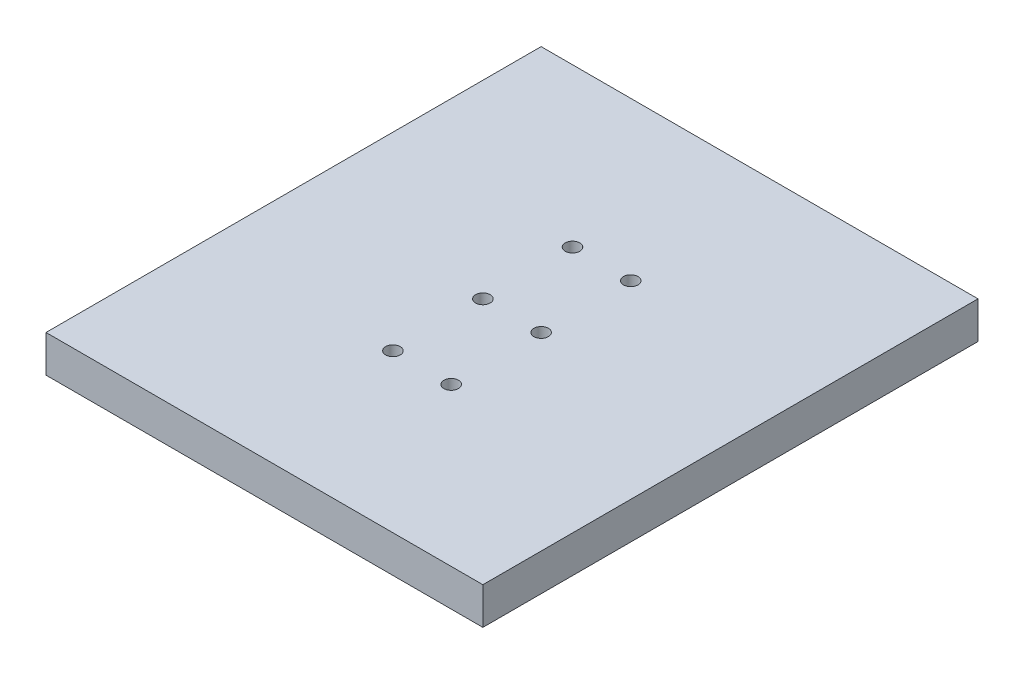
SolidWorks part; units mm, degrees
material "Aleación 1060"
ref_plane "Alzado" through (0, 0, 0) normal (0, 0, 1) x (1, 0, 0)
ref_plane "Planta" through (0, 0, 0) normal (0, 1, 0) x (1, 0, 0)
ref_plane "Vista lateral" through (0, 0, 0) normal (1, 0, 0) x (0, 0, -1)
sketch "Croquis1" plane through (0, 0, 0) normal (0, 1, 0) x (1, 0, 0)
  line L0 (10, 85) -> (10, -85) construction
  line L1 (75, -85) -> (-75, -85)
  line L2 (75, -85) -> (75, 85)
  line L3 (75, 85) -> (-75, 85)
  line L4 (-75, -85) -> (-75, 85)
  line L5 (75, -85) -> (-75, 85) construction
  line L6 (75, 85) -> (-75, -85) construction
  line L7 (-10, 85) -> (-10, -85) construction
  circle A0 centre (10, 0) radius 2.5013
  circle A1 centre (-10, 0) radius 2.5
  circle A2 centre (10, 30.7698) radius 2.5
  circle A3 centre (-10, 30.7698) radius 2.5
  circle A4 centre (10, -30.8842) radius 2.5
  circle A5 centre (-10, -30.8842) radius 2.5
  point P0 (0, 0)
  dimension "D1" = 170
  dimension "D2" = 150
  dimension "D3" = 20
  dimension "D4" = 20
extrude "Saliente-Extruir1" add sketch "Croquis1" along normal blind 12.7
